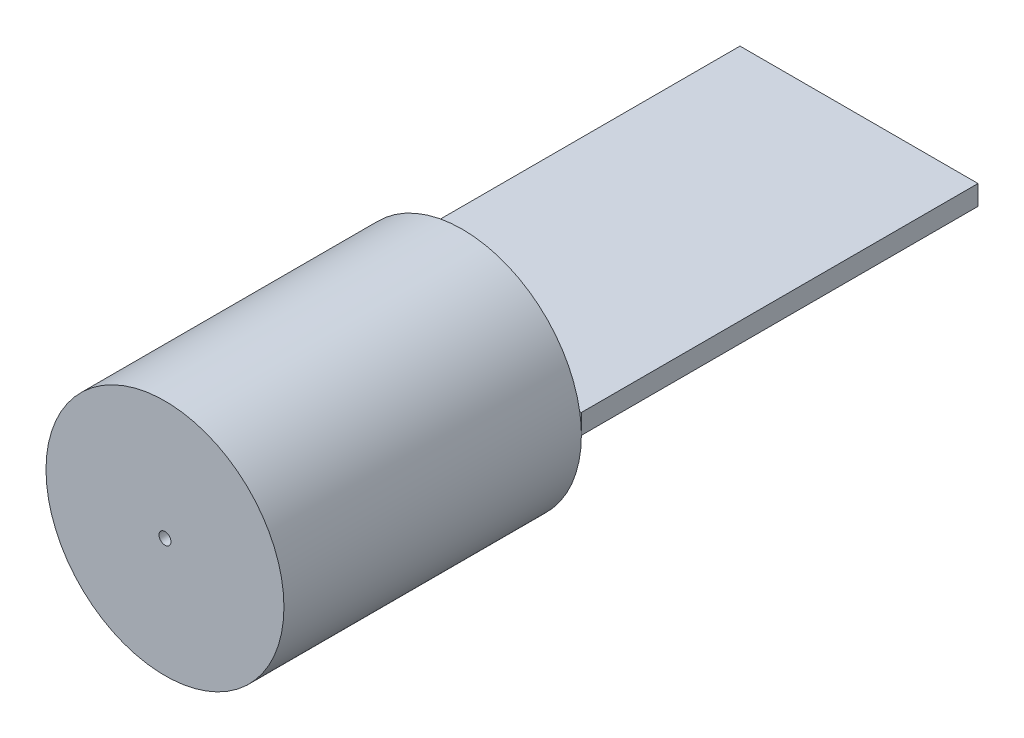
SolidWorks part; units mm, degrees
ref_plane "Plan de face" through (0, 0, 0) normal (0, 0, 1) x (1, 0, 0)
ref_plane "Plan de dessus" through (0, 0, 0) normal (0, 1, 0) x (1, 0, 0)
ref_plane "Plan de droite" through (0, 0, 0) normal (1, 0, 0) x (0, 0, -1)
sketch "Esquisse1" plane through (0, 0, 0) normal (0, 0, 1) x (1, 0, 0)
  circle A0 centre (0, 0) radius 6
  dimension "D1" = 12
extrude "Boss.-Extru.1" add sketch "Esquisse1" along normal blind 15
sketch "Esquisse2" plane through (0, 0, 15) normal (0, 0, 1) x (1, 0, 0)
  circle A0 centre (0, 0) radius 0.3
  dimension "D1" = 0.6
extrude "Enlèv. mat.-Extru.1" cut sketch "Esquisse2" against normal blind 3
sketch "Esquisse3" plane through (0, 0, 0) normal (0, 1, 0) x (1, 0, 0)
  line L1 (-6, 0) -> (6.0033, 0)
  line L2 (-6, 0) -> (-6, 20)
  line L3 (-6, 20) -> (6.0033, 20)
  line L4 (6.0033, 0) -> (6.0033, 20)
  dimension "D1" = 20
extrude "Boss.-Extru.2" add sketch "Esquisse3" along normal blind 1
